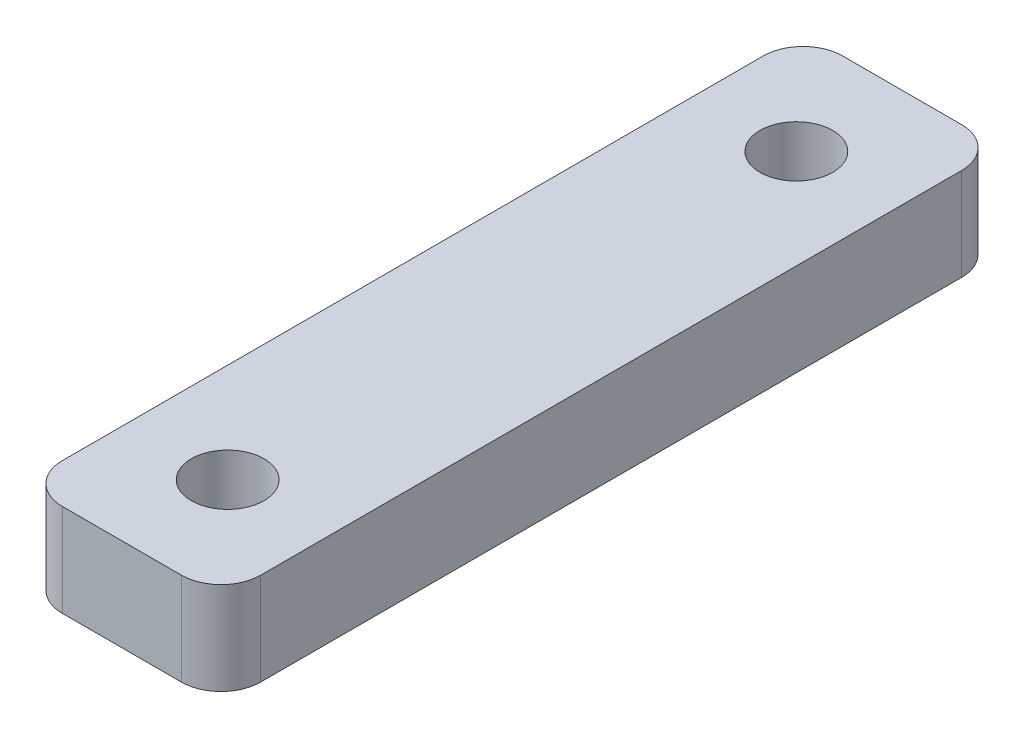
SolidWorks part; units mm, degrees
ref_plane "Front Plane" through (0, 0, 0) normal (0, 0, 1) x (1, 0, 0)
ref_plane "Top Plane" through (0, 0, 0) normal (0, 1, 0) x (1, 0, 0)
ref_plane "Right Plane" through (0, 0, 0) normal (1, 0, 0) x (0, 0, -1)
sketch "Sketch1" plane through (0, 0, 0) normal (0, 1, 0) x (1, 0, 0)
  line L0 (0, 0) -> (0, 53)
  line L1 (3, 56) -> (12, 56)
  line L2 (15, 53) -> (15, 0)
  line L3 (12, -3) -> (3, -3)
  arc A0 (0, 53) -> (3, 56) centre (3, 53) cw
  arc A1 (12, 56) -> (15, 53) centre (12, 53) cw
  arc A2 (15, 0) -> (12, -3) centre (12, 0) cw
  arc A3 (3, -3) -> (0, 0) centre (3, 0) cw
  circle A4 centre (7.5, 48) radius 2.75
  circle A5 centre (7.5, 5) radius 2.75
  dimension "D2" = 3
  dimension "D3" = 3
  dimension "D4" = 3
  dimension "D5" = 3
  dimension "D9" = 5.5
  dimension "D10" = 5.5
  dimension "D13" = 43
  dimension "D6" = 15
  dimension "D7" = 8
  dimension "D8" = 7.5
  dimension "D11" = 7.5
  dimension "D12" = 8
extrude "Boss-Extrude1" add sketch "Sketch1" along normal blind 7
